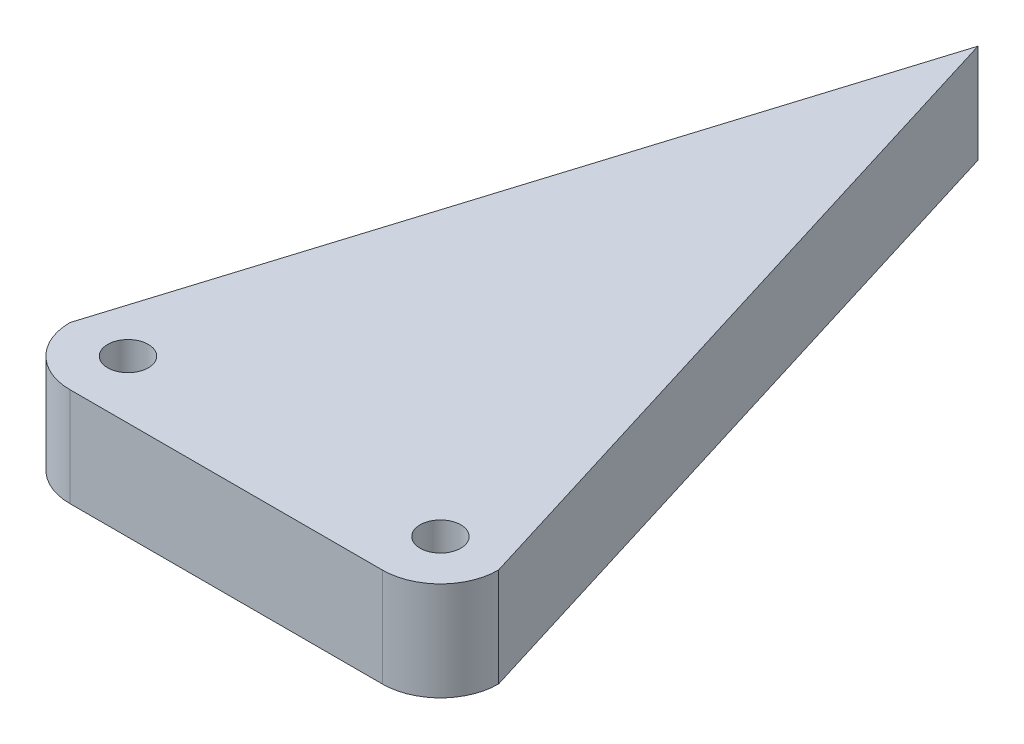
SolidWorks part; units mm, degrees
ref_plane "Front Plane" through (0, 0, 0) normal (0, 0, 1) x (1, 0, 0)
ref_plane "Top Plane" through (0, 0, 0) normal (0, 1, 0) x (1, 0, 0)
ref_plane "Right Plane" through (0, 0, 0) normal (1, 0, 0) x (0, 0, -1)
sketch "Sketch1" plane through (0, 0, 0) normal (0, 1, 0) x (1, 0, 0)
  line L2 (-5, 0) -> (13.4798, 59.697)
  line L3 (13.4798, 59.697) -> (31.9, 0)
  line L4 (0, -5) -> (26.9, -5)
  circle A0 centre (0, 0) radius 1.75
  circle A1 centre (26.9, 0) radius 1.75
  arc A2 (-5, 0) -> (0, -5) centre (0, 0) ccw
  arc A3 (26.9, -5) -> (31.9, 0) centre (26.9, 0) ccw
extrude "Boss-Extrude3" add sketch "Sketch1" along normal blind 8.5
sketch "Sketch4" plane through (0, 8.5, 0) normal (0, 1, 0) x (1, 0, 0)
  line L0 (13.45, -5) -> (13.45, 10.0456)
  line L1 (0, -5) -> (26.9, -5) construction
sketch "Sketch5" plane through (29.1268, 0, -8.9874) normal (0.9555, 0, -0.2948) x (-0.2948, 0, -0.9555)
  line L0 (53.0688, 8.5) -> (53.0688, 0) construction
  point P0 (53.0688, 4.25)
